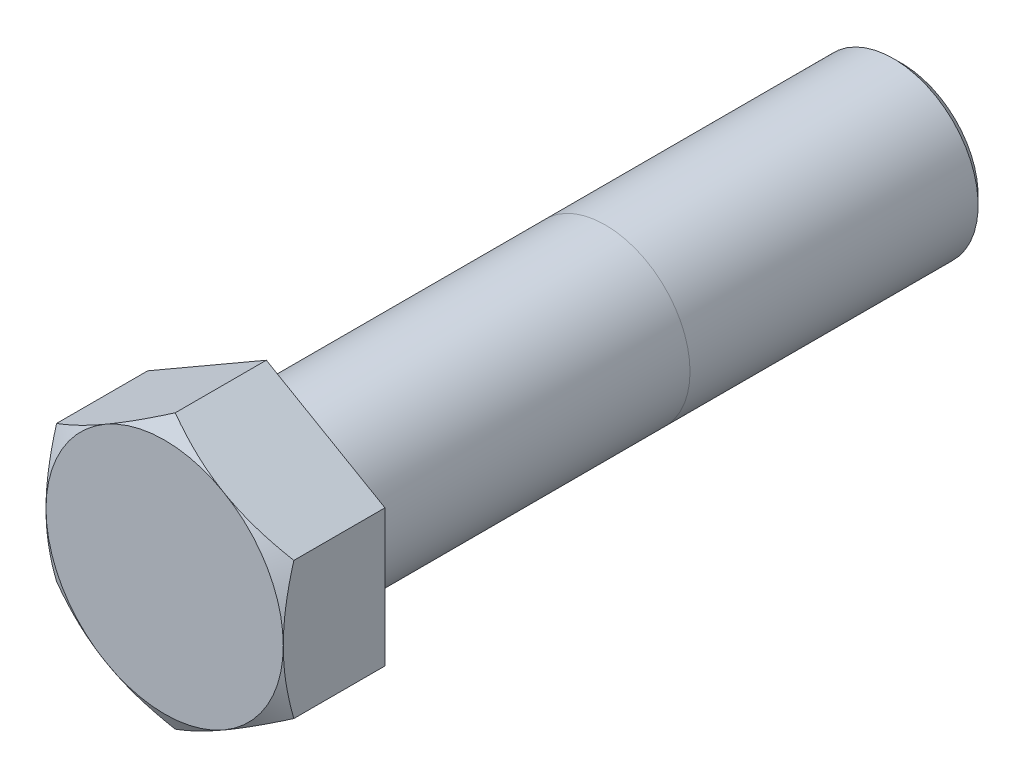
SolidWorks part; units mm, degrees
ref_plane "Front Plane" through (0, 0, 0) normal (0, 0, 1) x (1, 0, 0)
ref_plane "Top Plane" through (0, 0, 0) normal (0, 1, 0) x (1, 0, 0)
ref_plane "Right Plane" through (0, 0, 0) normal (1, 0, 0) x (0, 0, -1)
sketch "Sketch1" plane through (0, 0, 0) normal (0, 0, 1) x (1, 0, 0)
  line L1 (0, -16.1658) -> (14, -8.0829)
  line L2 (14, -8.0829) -> (14, 8.0829)
  line L3 (14, 8.0829) -> (0, 16.1658)
  line L4 (0, 16.1658) -> (-14, 8.0829)
  line L5 (-14, 8.0829) -> (-14, -8.0829)
  line L6 (-14, -8.0829) -> (0, -16.1658)
  circle A0 centre (0, 0) radius 14 construction
  dimension "D1" = 28
extrude "Boss-Extrude1" add sketch "Sketch1" along normal blind 12
sketch "Sketch2" plane through (0, 0, 12) normal (0, 0, 1) x (1, 0, 0)
  line L0 (14, 8.0829) -> (0, 16.1658) construction
  circle A0 centre (0, 0) radius 14
extrude "Cut-Extrude1" cut sketch "Sketch2" against normal blind 12 draft 60 flip side to cut
sketch "Sketch3" plane through (0, 0, 0) normal (0, 0, -1) x (-1, 0, 0)
  circle A0 centre (0, 0) radius 10
  dimension "D1" = 20
extrude "Boss-Extrude2" add sketch "Sketch3" along normal blind 75
chamfer "Chamfer1" distance 1 angle 45 1 edges at (-10, 0, -75)
sketch "Sketch4" plane through (0, 0, 0) normal (0, 1, 0) x (1, 0, 0)
  line L0 (-10, 40) -> (10, 40)
  line L1 (-10, 74) -> (-10, 0) construction
  line L2 (10, 0) -> (10, 74) construction
  line L3 (14, 0) -> (0, 0) construction
  dimension "D1" = 40
split line "Split Line1"
